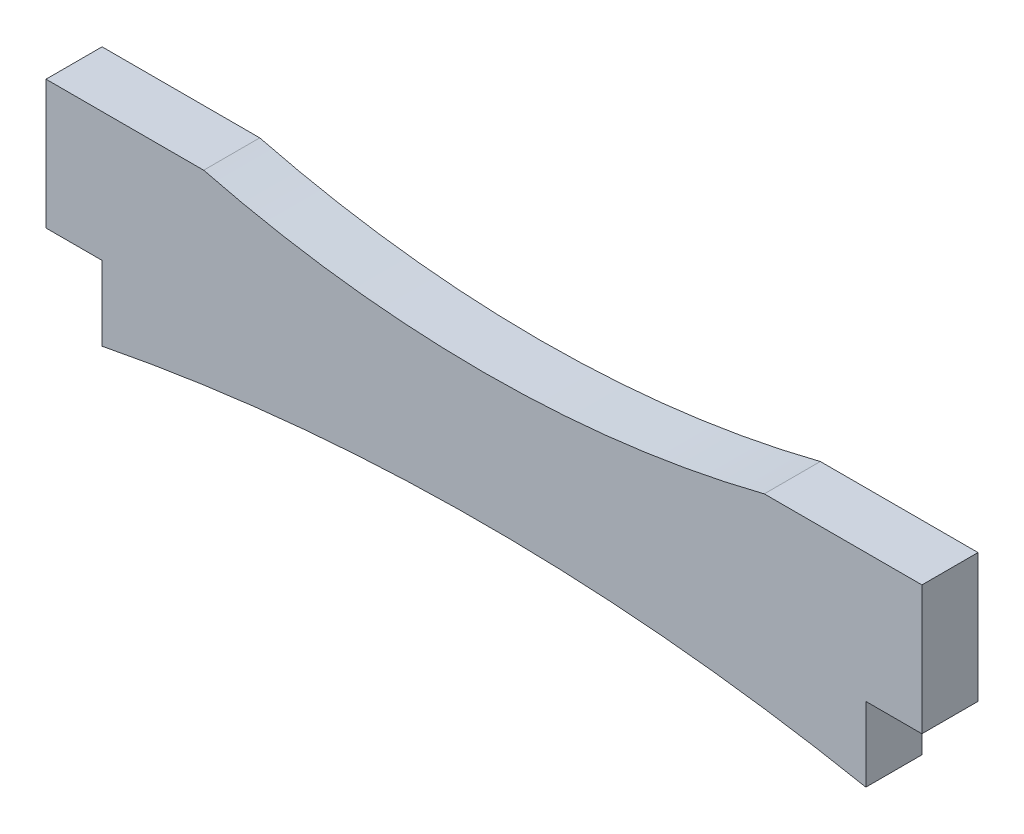
SolidWorks part; units mm, degrees
ref_plane "Plan de face" through (0, 0, 0) normal (0, 0, 1) x (1, 0, 0)
ref_plane "Plan de dessus" through (0, 0, 0) normal (0, 1, 0) x (1, 0, 0)
ref_plane "Plan de droite" through (0, 0, 0) normal (1, 0, 0) x (0, 0, -1)
sketch "Esquisse1" plane through (0, 0, 0) normal (0, 0, 1) x (1, 0, 0)
  line L0 (-62.5, 0) -> (62.5, 0) construction
  line L1 (-62.5, 9.1991) -> (-62.5, -9.1991)
  line L2 (-62.5, -9.1991) -> (-54.5, -9.1991)
  line L3 (-54.5, -9.1991) -> (-54.5, -19.8009)
  line L4 (0, -14.5) -> (0, 9.5) construction
  line L5 (54.5, -9.1991) -> (54.5, -19.8009)
  line L6 (62.5, -9.1991) -> (54.5, -9.1991)
  line L7 (62.5, 9.1991) -> (62.5, -9.1991)
  line L8 (-62.5, 9.1991) -> (-40, 9.1991)
  line L9 (62.5, 9.1991) -> (40, 9.1991)
  line L10 (-54.5, -14.5) -> (54.5, -14.5) construction
  line L11 (-62.5, 4.1991) -> (62.5, 4.1991) construction
  arc A0 (-54.5, -19.8009) -> (54.5, -19.8009) centre (0, -297.3127) cw
  arc A1 (-40, 9.1991) -> (40, 9.1991) centre (0, 166.699) ccw
  dimension "D1" = 5
  dimension "D2" = 109
  dimension "D3" = 8
extrude "Boss.-Extru.1" add sketch "Esquisse1" along normal blind 8
